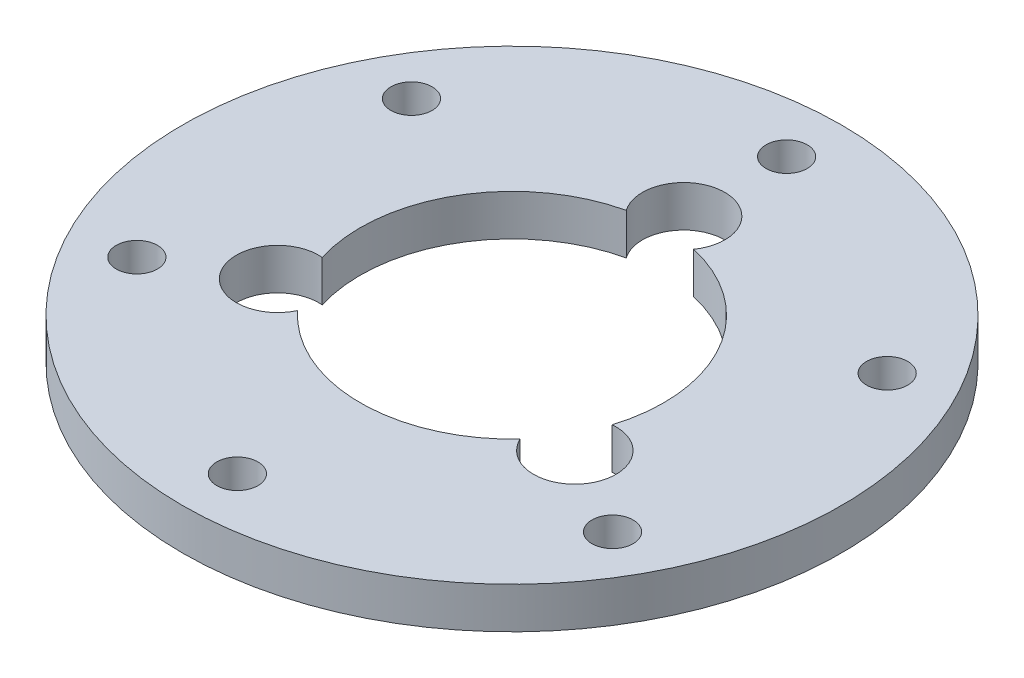
SolidWorks part; units mm, degrees
material "玻纤"
ref_plane "前视基准面" through (0, 0, 0) normal (0, 0, 1) x (1, 0, 0)
ref_plane "上视基准面" through (0, 0, 0) normal (0, 1, 0) x (1, 0, 0)
ref_plane "右视基准面" through (0, 0, 0) normal (1, 0, 0) x (0, 0, -1)
sketch "草图1" plane through (0, 0, 0) normal (0, 1, 0) x (1, 0, 0)
  circle A0 centre (0, 0) radius 24
  circle A1 centre (0, 0) radius 11.05
  circle A2 centre (0, 0) radius 20 construction
  circle A3 centre (0, 0) radius 12.5 construction
  circle A4 centre (0, 20) radius 1.5
  circle A5 centre (0, 12.5) radius 1.4
  circle A6 centre (17.3205, 10) radius 1.5
  circle A7 centre (17.3205, -10) radius 1.5
  circle A8 centre (0, -20) radius 1.5
  circle A9 centre (-17.3205, -10) radius 1.5
  circle A10 centre (-17.3205, 10) radius 1.5
  circle A11 centre (10.8253, -6.25) radius 1.4
  circle A12 centre (-10.8253, -6.25) radius 1.4
  dimension "D1" = 22.1
  dimension "D2" = 48
  dimension "D3" = 40
  dimension "D4" = 25
  dimension "D5" = 3
  dimension "D7" = 2.8
  dimension "D6" = 6
  dimension "D8" = 3
extrude "凸台-拉伸1" add sketch "草图1" along normal blind 3
sketch "草图2" plane through (0, 0, 0) normal (0, -1, 0) x (1, 0, 0)
  circle A0 centre (10.8253, 6.25) radius 3
  circle A1 centre (-10.8253, 6.25) radius 3
  circle A2 centre (0, -12.5) radius 3
  dimension "D1" = 6
  dimension "D2" = 6
  dimension "D3" = 6
extrude "切除-拉伸1" cut sketch "草图2" against normal blind 10
